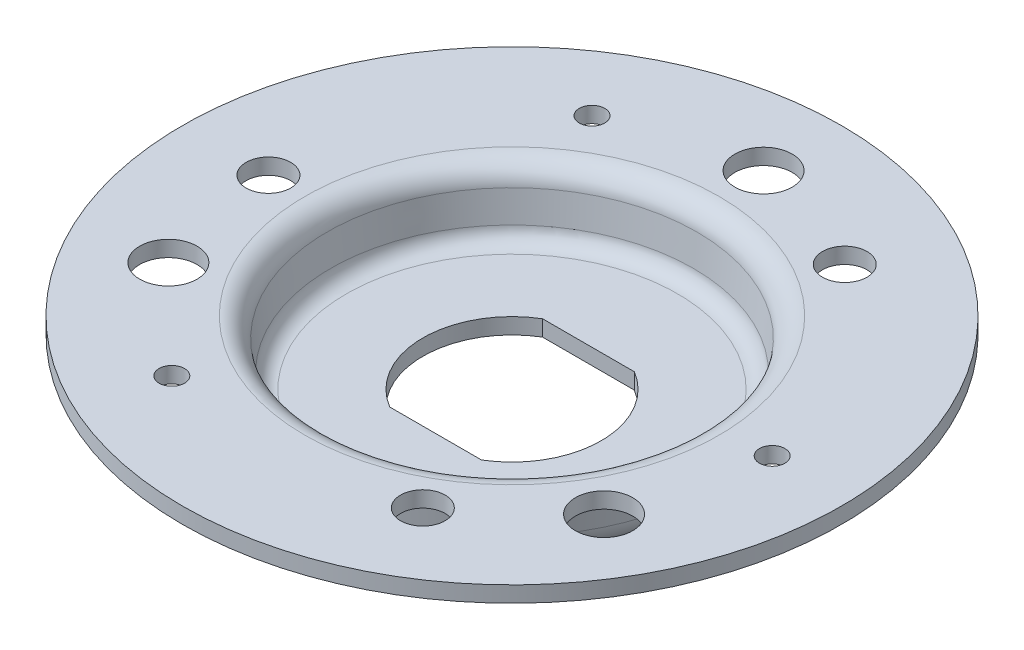
SolidWorks part; units mm, degrees
material "ASTM A36"
ref_plane "Plano frontal" through (0, 0, 0) normal (0, 0, 1) x (1, 0, 0)
ref_plane "Plano superior" through (0, 0, 0) normal (0, 1, 0) x (1, 0, 0)
ref_plane "Plano direito" through (0, 0, 0) normal (1, 0, 0) x (0, 0, -1)
sketch "Esboço1" plane through (0, 0, 0) normal (1, 0, 0) x (0, 0, -1)
  line L0 (-12, 0) -> (-26, 0)
  line L1 (-30.9672, 4.4283) -> (-31.5066, 9.1143)
  line L2 (-32.5, 10) -> (-51.75, 10)
  line L3 (0, 0) -> (0, -45247.1508) construction
  line L4 (-12, 2.5) -> (-26, 2.5)
  line L5 (-28.4836, 4.7141) -> (-29.023, 9.4002)
  line L6 (-32.5, 12.5) -> (-51.75, 12.5)
  line L7 (-12, 2.5) -> (-12, 0)
  line L8 (-51.75, 12.5) -> (-51.75, 10)
  arc A0 (-26, 0) -> (-30.9672, 4.4283) centre (-26, 5) cw
  arc A1 (-31.5066, 9.1143) -> (-32.5, 10) centre (-32.5, 9) ccw
  arc A2 (-26, 2.5) -> (-28.4836, 4.7141) centre (-26, 5) cw
  arc A3 (-29.023, 9.4002) -> (-32.5, 12.5) centre (-32.5, 9) ccw
  dimension "D4" = 1
  dimension "D5" = 5
  dimension "D1" = 24
  dimension "D2" = 103.5
  dimension "D3" = 10
  dimension "D6" = 52
  dimension "D7" = 65
  dimension "D8" = 2.5
revolve "Revolução1" add sketch "Esboço1" angle 360 about L3
sketch "Esboço2" plane through (0, 2.5, 0) normal (0, 1, 0) x (1, 0, 0)
  line L0 (-7.2111, 12) -> (7.2111, 12)
  line L1 (0, 0) -> (-43.0631, 0) construction
  line L2 (-7.2111, -12) -> (7.2111, -12)
  line L3 (0, 39.5) -> (0, 0) construction
  line L4 (0, 0) -> (-20.9318, 33.4979) construction
  line L5 (0, 0) -> (20.875, 36.1566) construction
  line L6 (20.875, 36.1566) -> (25.875, 44.8168) construction
  arc A0 (-7.2111, 12) -> (-7.2111, -12) centre (0, 0) ccw
  circle A1 centre (0, 0) radius 12 construction
  arc A2 (7.2111, -12) -> (7.2111, 12) centre (0, 0) ccw
  circle A3 centre (0, 39.5) radius 4.5
  circle A4 centre (-20.9318, 33.4979) radius 2
  circle A5 centre (0, 0) radius 39.5 construction
  circle A6 centre (19.125, 33.1255) radius 3.5
  circle A7 centre (0, 0) radius 51.75 construction
  circle A8 centre (0, 0) radius 38.25 construction
  circle A9 centre (19.125, -33.1255) radius 3.5
  circle A10 centre (34.208, -19.75) radius 4.5
  circle A11 centre (39.4759, 1.3785) radius 2
  circle A12 centre (-38.25, 0) radius 3.5
  circle A13 centre (-34.208, -19.75) radius 4.5
  circle A14 centre (-18.5441, -34.8764) radius 2
  point P35 (0, 0)
  dimension "D1" = 14
  dimension "D2" = 79
  dimension "D3" = 9
  dimension "D4" = 4
  dimension "D5" = 32
  dimension "D6" = 7
  dimension "D7" = 30
  dimension "D8" = 76.5
  dimension "D9" = 3
extrude "Corte-extrusão1" cut sketch "Esboço2" against normal through all both and the other way through all
